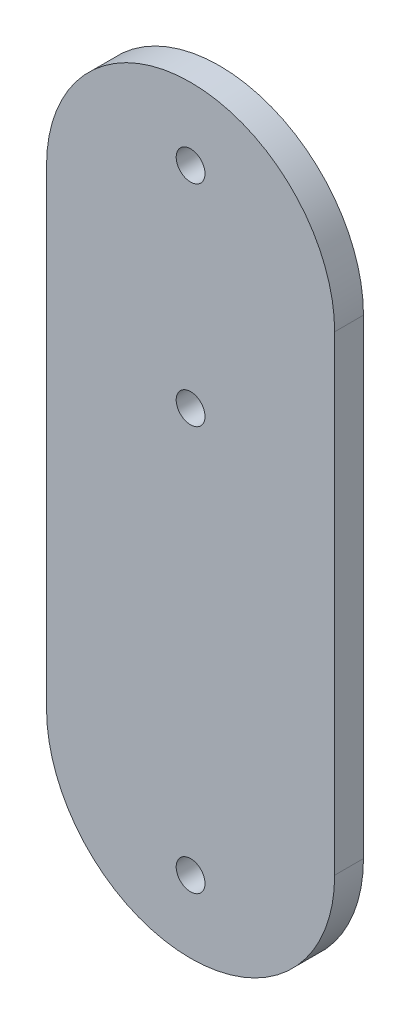
SolidWorks part; units mm, degrees
ref_plane "Front Plane" through (0, 0, 0) normal (0, 0, 1) x (1, 0, 0)
ref_plane "Top Plane" through (0, 0, 0) normal (0, 1, 0) x (1, 0, 0)
ref_plane "Right Plane" through (0, 0, 0) normal (1, 0, 0) x (0, 0, -1)
sketch "Sketch1" plane through (0, 0, 0) normal (0, 0, 1) x (1, 0, 0)
  line L0 (10, -983.573) -> (10, 49016.427) construction
  line L1 (0, 0) -> (20, 0) construction
  line L2 (0, 0) -> (0, 40.5) construction
  line L3 (0, 40.5) -> (20, 40.5) construction
  line L4 (20, 0) -> (20, 40.5) construction
  line L5 (-5, 44.75) -> (-5, -4.25)
  line L6 (25, 44.75) -> (25, -4.25)
  line L7 (-15.829, 44.75) -> (37.8977, 44.75) construction
  line L8 (37.8977, -4.25) -> (-13.7927, -4.25) construction
  line L9 (-1013.8926, 30.36) -> (48986.1074, 30.36) construction
  circle A0 centre (10, 52.25) radius 1.5
  circle A1 centre (10, -11.75) radius 1.5
  arc A2 (25, 44.75) -> (-5, 44.75) centre (10, 44.75) ccw
  arc A3 (-5, -4.25) -> (25, -4.25) centre (10, -4.25) ccw
  circle A4 centre (10, 30.36) radius 1.5
  dimension "D3" = 3
  dimension "D4" = 3
  dimension "D8" = 10.14
  dimension "D12" = 3
  dimension "D1" = 40.5
  dimension "D2" = 20
  dimension "D5" = 11.75
  dimension "D6" = 11.75
  dimension "D7" = 5
  dimension "D9" = 4.25
  dimension "D10" = 4.25
  dimension "D11" = 10
extrude "Boss-Extrude1" add sketch "Sketch1" along normal blind 3
